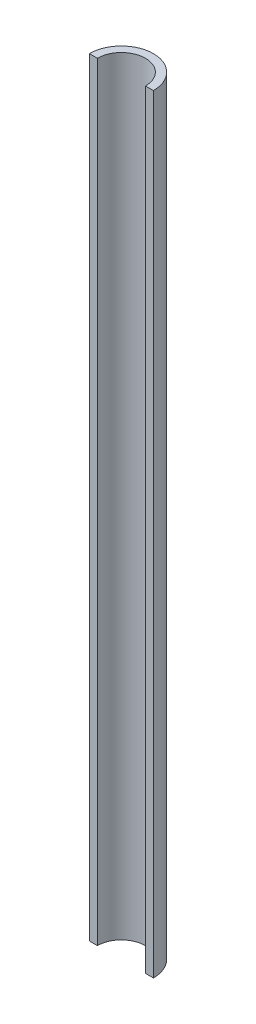
SolidWorks part; units mm, degrees
material "PTFE (general)"
ref_plane "Front Plane" through (0, 0, 0) normal (0, 0, 1) x (1, 0, 0)
ref_plane "Top Plane" through (0, 0, 0) normal (0, 1, 0) x (1, 0, 0)
ref_plane "Right Plane" through (0, 0, 0) normal (1, 0, 0) x (0, 0, -1)
sketch "Sketch1" plane through (0, 0, 0) normal (0, 1, 0) x (1, 0, 0)
  line L0 (-55, 0) -> (55, 0) construction
  line L1 (-3.175, 0) -> (-2.3813, 0)
  line L2 (2.3813, 0) -> (3.175, 0)
  arc A0 (-2.3813, 0) -> (2.3813, 0) centre (0, 0) cw
  arc A1 (-3.175, 0) -> (3.175, 0) centre (0, 0) cw
  dimension "D1" = 4.7625
  dimension "D2" = 6.35
extrude "Boss-Extrude1" add sketch "Sketch1" along normal blind 76.2
